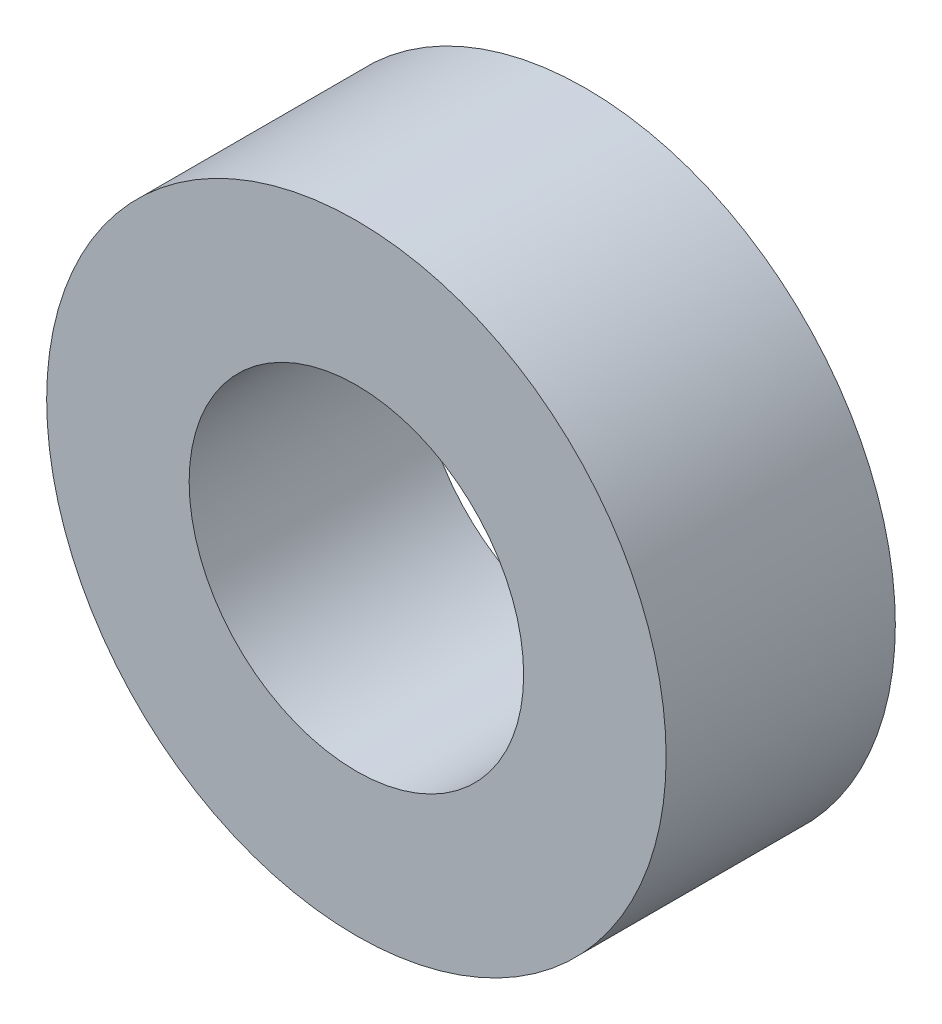
SolidWorks part; units mm, degrees
ref_plane "Front Plane" through (0, 0, 0) normal (0, 0, 1) x (1, 0, 0)
ref_plane "Top Plane" through (0, 0, 0) normal (0, 1, 0) x (1, 0, 0)
ref_plane "Right Plane" through (0, 0, 0) normal (1, 0, 0) x (0, 0, -1)
sketch "Sketch1" plane through (0, 0, 0) normal (0, 0, 1) x (1, 0, 0)
  circle A0 centre (0, 0) radius 3.429
  circle A1 centre (0, 0) radius 6.35
  dimension "D1" = 6.858
  dimension "D2" = 12.7
extrude "Boss-Extrude1" add sketch "Sketch1" along normal blind 4.699
